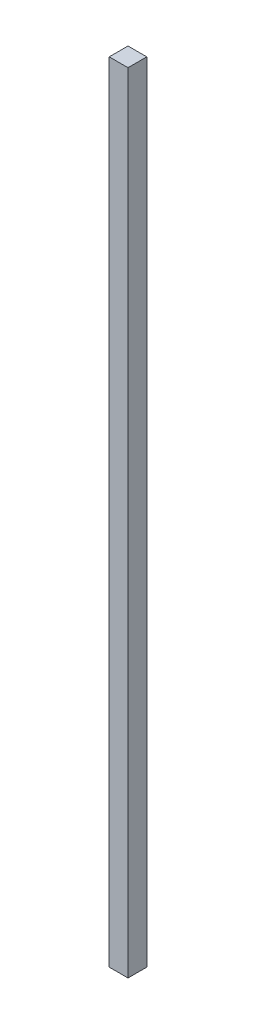
SolidWorks part; units mm, degrees
ref_plane "Front Plane" through (0, 0, 0) normal (0, 0, 1) x (1, 0, 0)
ref_plane "Top Plane" through (0, 0, 0) normal (0, 1, 0) x (1, 0, 0)
ref_plane "Right Plane" through (0, 0, 0) normal (1, 0, 0) x (0, 0, -1)
other "Configuration Table"
sketch "Sketch1" plane through (0, 0, 0) normal (0, 0, 1) x (1, 0, 0)
  line L1 (620, 120) -> (660, 120)
  line L2 (620, 120) -> (620, 1800)
  line L3 (620, 1800) -> (660, 1800)
  line L4 (660, 120) -> (660, 1800)
extrude "OVEN_firin_arka_kanal_kablo_1" add sketch "Sketch1" against normal blind 40 from offset 760 separate body
